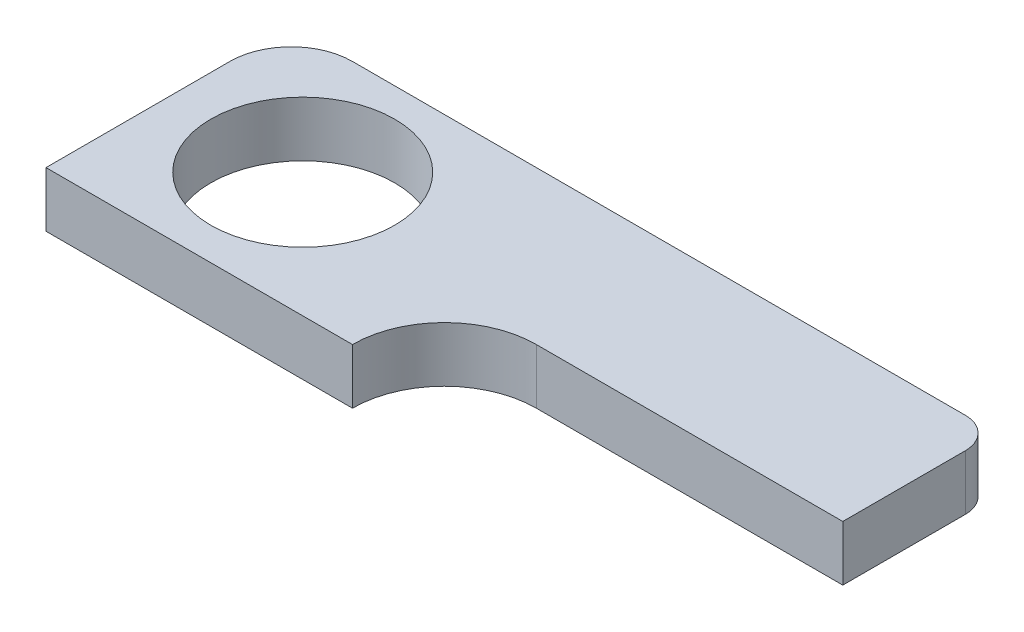
SolidWorks part; units mm, degrees
ref_plane "Front Plane" through (0, 0, 0) normal (0, 0, 1) x (1, 0, 0)
ref_plane "Top Plane" through (0, 0, 0) normal (0, 1, 0) x (1, 0, 0)
ref_plane "Right Plane" through (0, 0, 0) normal (1, 0, 0) x (0, 0, -1)
ref_plane "Plane1" through (0, 0, 0) normal (0, -1, 0) x (1, 0, 0)
sketch "Sketch1" plane through (0, 0, 0) normal (0, -1, 0) x (1, 0, 0)
  line L0 (230, -50) -> (130, -50)
  line L1 (100, -20) -> (0, -20)
  line L2 (0, -20) -> (0, -80)
  line L3 (20, -100) -> (220, -100)
  line L4 (230, -90) -> (230, -50)
  circle A0 centre (43.1853, -60.5874) radius 30
  arc A1 (130, -50) -> (100, -20) centre (130, -20) cw
  arc A2 (0, -80) -> (20, -100) centre (20, -80) ccw
  arc A3 (220, -100) -> (230, -90) centre (220, -90) ccw
extrude "Boss-Extrude1" add sketch "Sketch1" against normal blind 18
